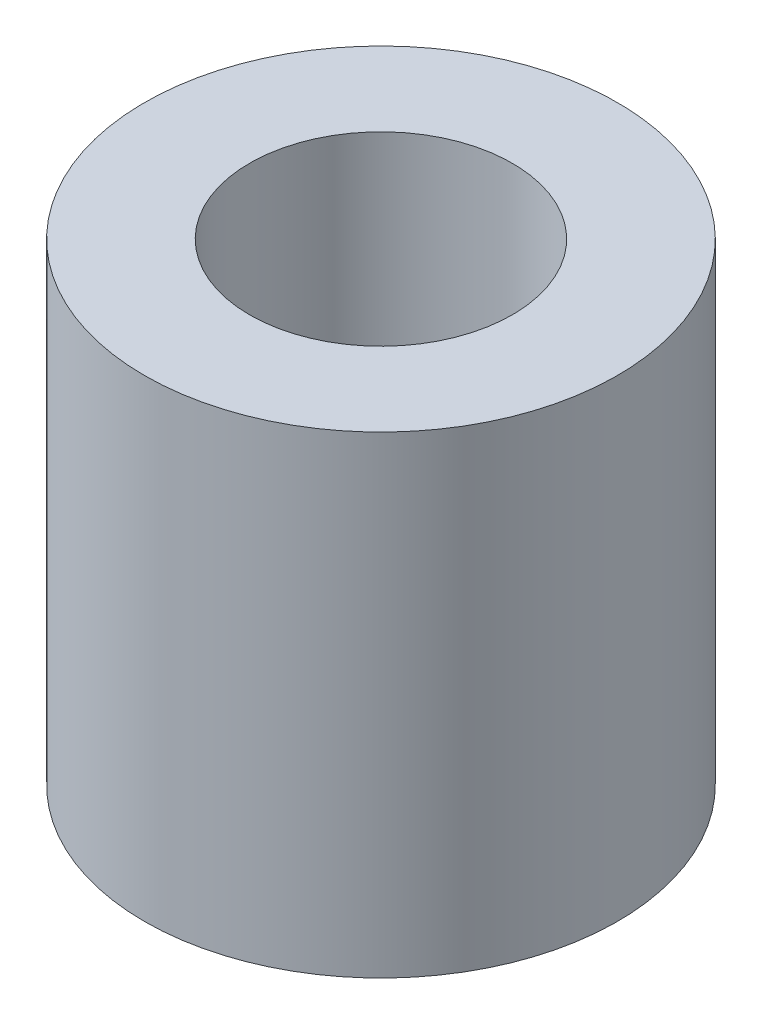
SolidWorks part; units mm, degrees
ref_plane "Front Plane" through (0, 0, 0) normal (0, 0, 1) x (1, 0, 0)
ref_plane "Top Plane" through (0, 0, 0) normal (0, 1, 0) x (1, 0, 0)
ref_plane "Right Plane" through (0, 0, 0) normal (1, 0, 0) x (0, 0, -1)
sketch "Sketch1" plane through (0, 0, 0) normal (0, 1, 0) x (1, 0, 0)
  circle A0 centre (0, 0) radius 2.5
  circle A1 centre (0, 0) radius 4.5
  dimension "D1" = 5
  dimension "D2" = 9
extrude "Boss-Extrude1" add sketch "Sketch1" along normal blind 9
